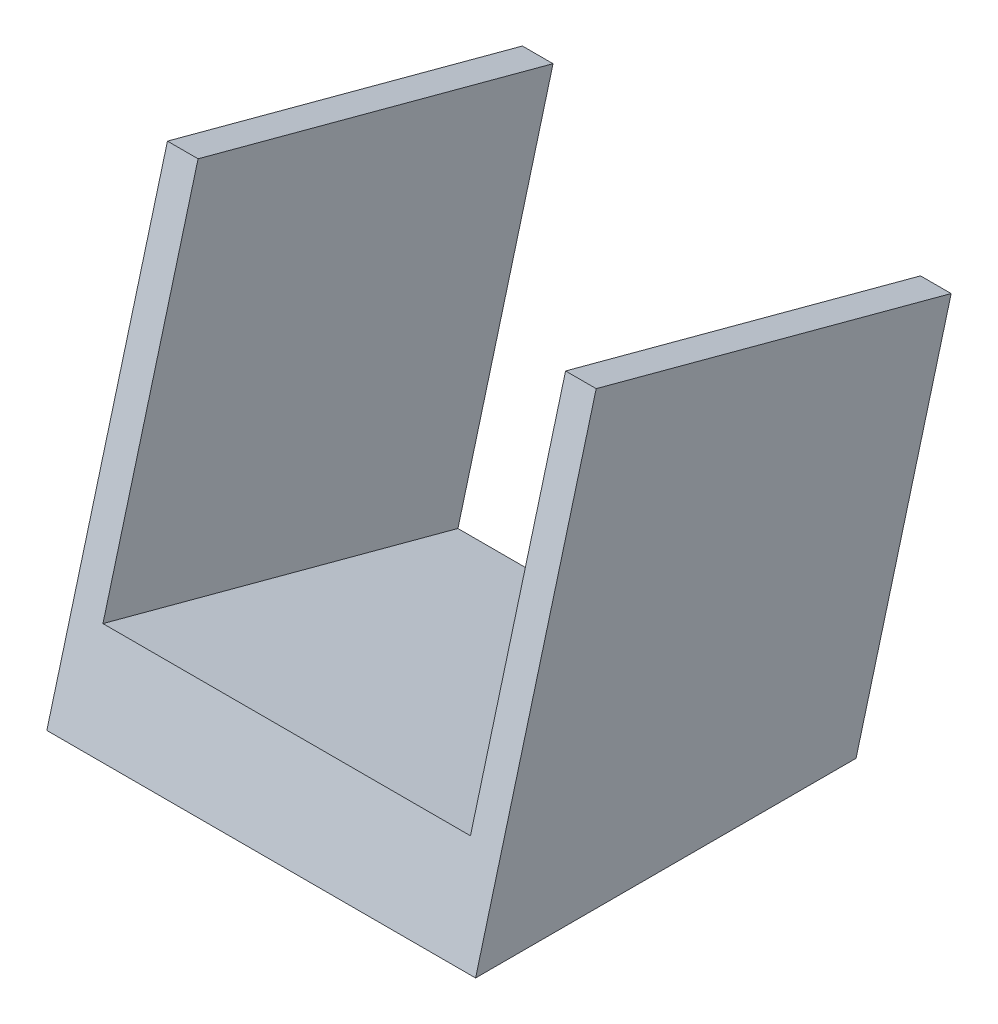
SolidWorks part; units mm, degrees
ref_plane "Front Plane" through (0, 0, 0) normal (0, 0, 1) x (1, 0, 0)
ref_plane "Top Plane" through (0, 0, 0) normal (0, 1, 0) x (1, 0, 0)
ref_plane "Right Plane" through (0, 0, 0) normal (1, 0, 0) x (0, 0, -1)
sketch "Sketch1" plane through (0, 0, 0) normal (1, 0, 0) x (0, 0, -1)
  line L0 (-39.444, 0) -> (39.444, 0)
  line L1 (39.444, 0) -> (59.166, 73.6035)
  line L2 (59.166, 73.6035) -> (-14.4375, 93.3256)
  line L3 (-14.4375, 93.3256) -> (-39.444, 0)
  point P2 (0, 0)
  dimension "D1" = 76.2
  dimension "D2" = 76.2
  dimension "D3" = 75
extrude "Boss-Extrude1" add sketch "Sketch1" along normal mid plane 88.9 contours L3 L0 L1 L2
sketch "Sketch2" plane through (0, 0, 0) normal (1, 0, 0) x (0, 0, -1)
  line L0 (-34.1595, 19.722) -> (-14.4375, 93.3256)
  line L1 (-34.1595, 19.722) -> (39.444, 0)
  line L2 (-14.4375, 93.3256) -> (59.166, 73.6035)
  line L3 (39.444, 0) -> (59.166, 73.6035)
  line L4 (-34.1595, 19.722) -> (59.166, 73.6035) construction
  line L5 (-14.4375, 93.3256) -> (39.444, 0) construction
  line L6 (-14.4375, 93.3256) -> (-39.444, 0) construction
  line L7 (39.444, 0) -> (59.166, 73.6035) construction
  line L8 (59.166, 73.6035) -> (-14.4375, 93.3256) construction
  point P1 (12.5033, 46.6628)
  dimension "D1" = 76.2
extrude "Cut-Extrude1" cut sketch "Sketch2" against normal mid plane 76.2
ref_plane "Plane1" through (0, 0, 0) normal (-1, 0, 0) x (0, 0, 1)
